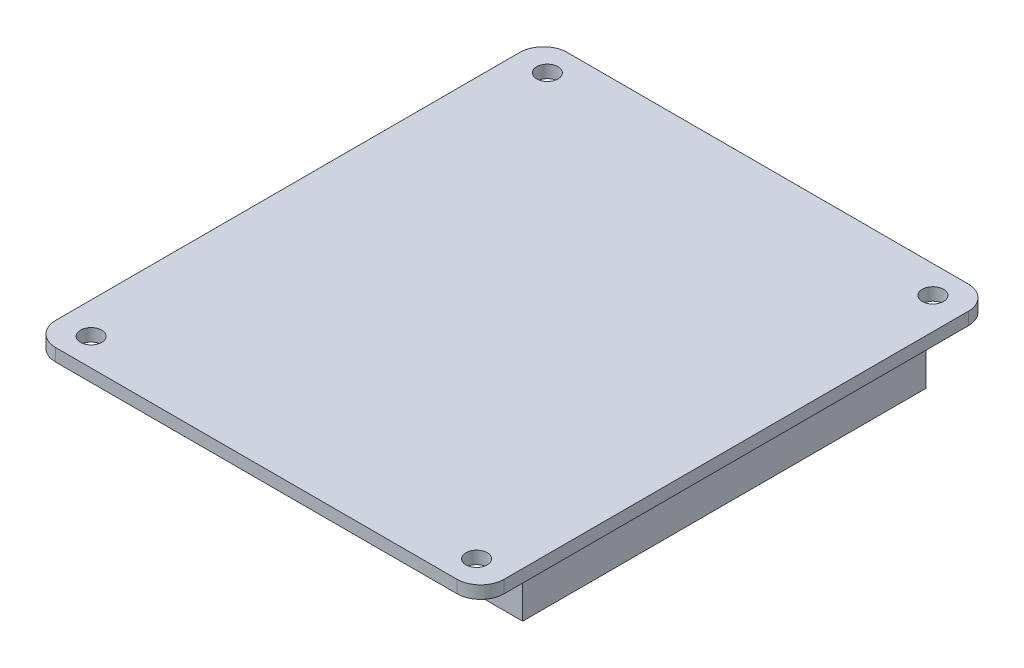
SolidWorks part; units mm, degrees
ref_plane "Front Plane" through (0, 0, 0) normal (0, 0, 1) x (1, 0, 0)
ref_plane "Top Plane" through (0, 0, 0) normal (0, 1, 0) x (1, 0, 0)
ref_plane "Right Plane" through (0, 0, 0) normal (1, 0, 0) x (0, 0, -1)
sketch "Sketch1" plane through (0, 0, 0) normal (0, 1, 0) x (1, 0, 0)
  line L1 (3, 0) -> (54, 0)
  line L2 (0, 3) -> (0, 62)
  line L3 (3, 65) -> (54, 65)
  line L4 (57, 3) -> (57, 62)
  arc A0 (3, 0) -> (0, 3) centre (3, 3) cw
  arc A1 (54, 0) -> (57, 3) centre (54, 3) ccw
  arc A2 (54, 65) -> (57, 62) centre (54, 62) cw
  arc A3 (0, 62) -> (3, 65) centre (3, 62) cw
  point P7 (0, 0)
  point P10 (57, 0)
  point P13 (57, 65)
  dimension "D3" = 3
  dimension "D1" = 57
  dimension "D2" = 65
extrude "Boss-Extrude1" add sketch "Sketch1" along normal blind 1.6
sketch "Sketch2" plane through (0, 1.6, 0) normal (0, 1, 0) x (1, 0, 0)
  line L0 (28.5, 65) -> (28.5, 0) construction
  line L1 (54, 65) -> (3, 65) construction
  line L2 (3, 0) -> (54, 0) construction
  line L3 (0, 32.5) -> (57, 32.5) construction
  line L4 (0, 62) -> (0, 3) construction
  line L5 (57, 3) -> (57, 62) construction
  line L7 (4, 61.5) -> (53, 61.5) construction
  line L8 (4, 61.5) -> (4, 3.5) construction
  line L9 (4, 3.5) -> (53, 3.5) construction
  line L10 (53, 61.5) -> (53, 3.5) construction
  circle A1 centre (4, 61.5) radius 1.35
  circle A2 centre (53, 61.5) radius 1.35
  circle A3 centre (53, 3.5) radius 1.35
  circle A4 centre (4, 3.5) radius 1.35
  point P16 (28.5, 61.5)
  point P17 (53, 32.5)
  dimension "D3" = 2.7
  dimension "D1" = 58
  dimension "D2" = 49
extrude "Cut-Extrude1" cut sketch "Sketch2" against normal through all
sketch "Sketch3" plane through (0, 0, 0) normal (0, -1, 0) x (1, 0, 0)
  line L0 (53, -61.5) -> (53, -3.5) construction
  line L1 (50.5, -58.15) -> (55.5, -58.15)
  line L2 (50.5, -58.15) -> (50.5, -6.85)
  line L3 (50.5, -6.85) -> (55.5, -6.85)
  line L4 (55.5, -58.15) -> (55.5, -6.85)
  line L5 (50.5, -32.5) -> (55.5, -32.5) construction
  point P9 (53, -32.5)
  point P10 (53, -32.5)
  dimension "D1" = 51.3
  dimension "D2" = 5
extrude "Boss-Extrude2" add sketch "Sketch3" along normal blind 5.7
sketch "Sketch4" plane through (0, 0, 0) normal (0, -1, 0) x (1, 0, 0)
  text T0 "LTE Base Hat"
